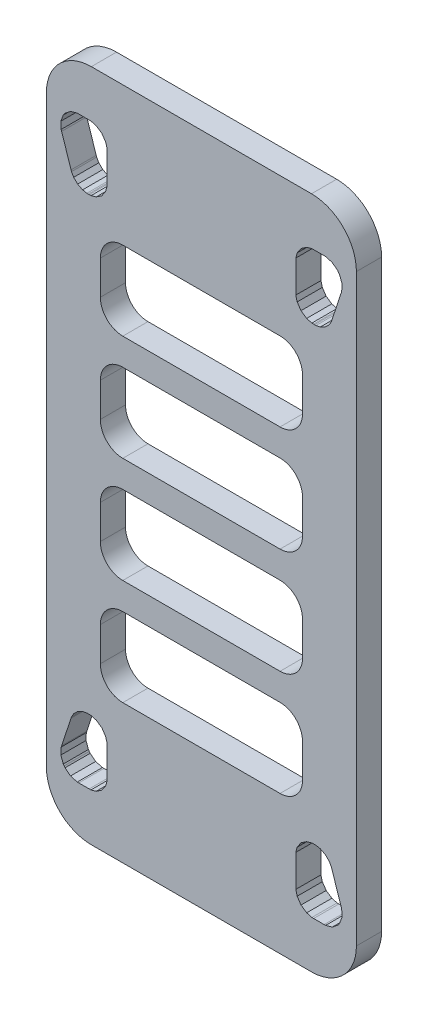
SolidWorks part; units mm, degrees
ref_plane "Front Plane" through (0, 0, 0) normal (0, 0, 1) x (1, 0, 0)
ref_plane "Top Plane" through (0, 0, 0) normal (0, 1, 0) x (1, 0, 0)
ref_plane "Right Plane" through (0, 0, 0) normal (1, 0, 0) x (0, 0, -1)
sketch "Model" plane through (0, 0, 0) normal (0, 0, 1) x (1, 0, 0)
  line L0 (59.6534, 200.5663) -> (102.2769, 95.4571) construction
  line L1 (59.6534, 95.4571) -> (102.2769, 200.5663) construction
  line L2 (58.4652, 168.561) -> (103.4652, 168.561)
  line L3 (46.4652, 73.0117) -> (115.4652, 73.0117)
  line L4 (46.4652, 73.0117) -> (46.4652, 223.0117)
  line L5 (46.4652, 223.0117) -> (115.4652, 223.0117)
  line L6 (115.4652, 73.0117) -> (115.4652, 223.0117)
  line L7 (46.4652, 73.0117) -> (115.4652, 223.0117) construction
  line L8 (46.4652, 223.0117) -> (115.4652, 73.0117) construction
  line L9 (58.4652, 192.1103) -> (103.4652, 192.1103)
  line L10 (58.4652, 192.1103) -> (58.4652, 174.561)
  line L11 (58.4652, 174.561) -> (103.4652, 174.561)
  line L12 (103.4652, 192.1103) -> (103.4652, 174.561)
  line L13 (58.4652, 168.561) -> (58.4652, 151.0117)
  line L14 (58.4652, 151.0117) -> (103.4652, 151.0117)
  line L15 (103.4652, 168.561) -> (103.4652, 151.0117)
  line L16 (46.4652, 148.0117) -> (115.4652, 148.0117) construction
  line L17 (103.4652, 127.4624) -> (103.4652, 145.0117)
  line L18 (58.4652, 145.0117) -> (103.4652, 145.0117)
  line L19 (58.4652, 127.4624) -> (58.4652, 145.0117)
  line L20 (103.4652, 103.9131) -> (103.4652, 121.4624)
  line L21 (58.4652, 121.4624) -> (103.4652, 121.4624)
  line L22 (58.4652, 103.9131) -> (58.4652, 121.4624)
  line L23 (58.4652, 103.9131) -> (103.4652, 103.9131)
  line L24 (58.4652, 127.4624) -> (103.4652, 127.4624)
  line L750 (105.9261, 198.1103) -> (106.1466, 198.1083)
  line L751 (106.1466, 198.1083) -> (106.4629, 198.1063)
  line L752 (106.4629, 198.1063) -> (107.4142, 198.2935)
  line L753 (107.4142, 198.2935) -> (108.5206, 198.8449)
  line L754 (108.5206, 198.8449) -> (109.3988, 199.7143)
  line L755 (109.3988, 199.7143) -> (109.8858, 200.5555)
  line L756 (109.8858, 200.5555) -> (109.985, 200.8552)
  line L757 (109.985, 200.8552) -> (112.0871, 207.2269)
  line L758 (112.0871, 207.2269) -> (112.1901, 207.5429)
  line L759 (112.1901, 207.5429) -> (112.252, 209.1014)
  line L760 (112.252, 209.1014) -> (111.7087, 210.5477)
  line L761 (111.7087, 210.5477) -> (111.5152, 210.8165)
  line L762 (111.5152, 210.8165) -> (111.32, 211.086)
  line L763 (111.32, 211.086) -> (110.0985, 212.0528)
  line L764 (110.0985, 212.0528) -> (108.5995, 212.4804)
  line L765 (108.5995, 212.4804) -> (108.269, 212.4799)
  line L766 (108.269, 212.4799) -> (105.9481, 212.4799)
  line L767 (105.9481, 212.4799) -> (105.5607, 212.4691)
  line L768 (105.5607, 212.4691) -> (104.3973, 212.1494)
  line L769 (104.3973, 212.1494) -> (103.1334, 211.2912)
  line L770 (103.1334, 211.2912) -> (102.2786, 210.0219)
  line L771 (102.2786, 210.0219) -> (101.9664, 208.8586)
  line L772 (101.9664, 208.8586) -> (101.9664, 208.4691)
  line L773 (101.9664, 208.4691) -> (101.9664, 202.1103)
  line L774 (101.9664, 202.1103) -> (101.9664, 201.7239)
  line L775 (101.9664, 201.7239) -> (102.2769, 200.5663)
  line L776 (102.2769, 200.5663) -> (103.124, 199.2987)
  line L777 (103.124, 199.2987) -> (104.3828, 198.4371)
  line L778 (104.3828, 198.4371) -> (105.5383, 198.1134)
  line L779 (105.5383, 198.1134) -> (105.9261, 198.1103)
  line L780 (56.0063, 198.1103) -> (55.7862, 198.1083)
  line L781 (55.7862, 198.1083) -> (55.4681, 198.1063)
  line L782 (55.4681, 198.1063) -> (54.5158, 198.2935)
  line L783 (54.5158, 198.2935) -> (53.4101, 198.8449)
  line L784 (53.4101, 198.8449) -> (52.5319, 199.7143)
  line L785 (52.5319, 199.7143) -> (52.0466, 200.5555)
  line L786 (52.0466, 200.5555) -> (51.9474, 200.8552)
  line L787 (51.9474, 200.8552) -> (49.8456, 207.2269)
  line L788 (49.8456, 207.2269) -> (49.741, 207.5429)
  line L789 (49.741, 207.5429) -> (49.6783, 209.1014)
  line L790 (49.6783, 209.1014) -> (50.2131, 210.5638)
  line L791 (50.2131, 210.5638) -> (50.4095, 210.8317)
  line L792 (50.4095, 210.8317) -> (50.6042, 211.1002)
  line L793 (50.6042, 211.1002) -> (51.8299, 212.0614)
  line L794 (51.8299, 212.0614) -> (53.3312, 212.482)
  line L795 (53.3312, 212.482) -> (53.6637, 212.4799)
  line L796 (53.6637, 212.4799) -> (55.984, 212.4799)
  line L797 (55.984, 212.4799) -> (56.37, 212.4818)
  line L798 (56.37, 212.4818) -> (57.5345, 212.1675)
  line L799 (57.5345, 212.1675) -> (58.8048, 211.3152)
  line L800 (58.8048, 211.3152) -> (59.6628, 210.0499)
  line L801 (59.6628, 210.0499) -> (59.9825, 208.8881)
  line L802 (59.9825, 208.8881) -> (59.9656, 208.4691)
  line L803 (59.9656, 208.4691) -> (59.9656, 202.1103)
  line L804 (59.9656, 202.1103) -> (59.9656, 201.7239)
  line L805 (59.9656, 201.7239) -> (59.6534, 200.5663)
  line L806 (59.6534, 200.5663) -> (58.8064, 199.2987)
  line L807 (58.8064, 199.2987) -> (57.5479, 198.4371)
  line L808 (57.5479, 198.4371) -> (56.3924, 198.1134)
  line L809 (56.3924, 198.1134) -> (56.0063, 198.1103)
  line L810 (105.9261, 97.9101) -> (106.1466, 97.9118)
  line L811 (106.1466, 97.9118) -> (106.4629, 97.9155)
  line L812 (106.4629, 97.9155) -> (107.4142, 97.7279)
  line L813 (107.4142, 97.7279) -> (108.5206, 97.1772)
  line L814 (108.5206, 97.1772) -> (109.3988, 96.3078)
  line L815 (109.3988, 96.3078) -> (109.8858, 95.4666)
  line L816 (109.8858, 95.4666) -> (109.985, 95.1648)
  line L817 (109.985, 95.1648) -> (112.0871, 88.7928)
  line L818 (112.0871, 88.7928) -> (112.1901, 88.4785)
  line L819 (112.1901, 88.4785) -> (112.252, 86.9227)
  line L820 (112.252, 86.9227) -> (111.7098, 85.4737)
  line L821 (111.7098, 85.4737) -> (111.5161, 85.203)
  line L822 (111.5161, 85.203) -> (111.3208, 84.934)
  line L823 (111.3208, 84.934) -> (110.0988, 83.9682)
  line L824 (110.0988, 83.9682) -> (108.5995, 83.5411)
  line L825 (108.5995, 83.5411) -> (108.269, 83.5415)
  line L826 (108.269, 83.5415) -> (105.9481, 83.5415)
  line L827 (105.9481, 83.5415) -> (105.5607, 83.553)
  line L828 (105.5607, 83.553) -> (104.3973, 83.8723)
  line L829 (104.3973, 83.8723) -> (103.1334, 84.7325)
  line L830 (103.1334, 84.7325) -> (102.2786, 86.0022)
  line L831 (102.2786, 86.0022) -> (101.9664, 87.1648)
  line L832 (101.9664, 87.1648) -> (101.9664, 87.5509)
  line L833 (101.9664, 87.5509) -> (101.9664, 93.9101)
  line L834 (101.9664, 93.9101) -> (101.9664, 94.2975)
  line L835 (101.9664, 94.2975) -> (102.2769, 95.4571)
  line L836 (102.2769, 95.4571) -> (103.124, 96.7234)
  line L837 (103.124, 96.7234) -> (104.3828, 97.5849)
  line L838 (104.3828, 97.5849) -> (105.5383, 97.9063)
  line L839 (105.5383, 97.9063) -> (105.9261, 97.9101)
  line L840 (56.0063, 97.9101) -> (55.7862, 97.9118)
  line L841 (55.7862, 97.9118) -> (55.4681, 97.9155)
  line L842 (55.4681, 97.9155) -> (54.5158, 97.7279)
  line L843 (54.5158, 97.7279) -> (53.4101, 97.1772)
  line L844 (53.4101, 97.1772) -> (52.5319, 96.3078)
  line L845 (52.5319, 96.3078) -> (52.0466, 95.4666)
  line L846 (52.0466, 95.4666) -> (51.9474, 95.1648)
  line L847 (51.9474, 95.1648) -> (49.8456, 88.7928)
  line L848 (49.8456, 88.7928) -> (49.741, 88.4785)
  line L849 (49.741, 88.4785) -> (49.6783, 86.9227)
  line L850 (49.6783, 86.9227) -> (50.2131, 85.4597)
  line L851 (50.2131, 85.4597) -> (50.4095, 85.1897)
  line L852 (50.4095, 85.1897) -> (50.6042, 84.9215)
  line L853 (50.6042, 84.9215) -> (51.8299, 83.9607)
  line L854 (51.8299, 83.9607) -> (53.3312, 83.5398)
  line L855 (53.3312, 83.5398) -> (53.6637, 83.5415)
  line L856 (53.6637, 83.5415) -> (55.984, 83.5415)
  line L857 (55.984, 83.5415) -> (56.37, 83.5419)
  line L858 (56.37, 83.5419) -> (57.5343, 83.8565)
  line L859 (57.5343, 83.8565) -> (58.8041, 84.7115)
  line L860 (58.8041, 84.7115) -> (59.6614, 85.9777)
  line L861 (59.6614, 85.9777) -> (59.9804, 87.1391)
  line L862 (59.9804, 87.1391) -> (59.982, 87.5251)
  line L863 (59.982, 87.5251) -> (59.982, 93.8843)
  line L864 (59.982, 93.8843) -> (59.982, 94.2717)
  line L865 (59.982, 94.2717) -> (59.6534, 95.4571)
  line L866 (59.6534, 95.4571) -> (58.8064, 96.7234)
  line L867 (58.8064, 96.7234) -> (57.5479, 97.5849)
  line L868 (57.5479, 97.5849) -> (56.3924, 97.9063)
  line L869 (56.3924, 97.9063) -> (56.0063, 97.9101)
  point P0 (80.9652, 148.0117)
  dimension "D5" = 6
  dimension "D6" = 6
  dimension "D7" = 3
  dimension "D1" = 69
  dimension "D2" = 12
  dimension "D3" = 150
  dimension "D4" = 12
extrude "Boss-Extrude1" add sketch "Model" along normal blind 5.6
fillet "Fillet1" radius 10 4 edges at (115.4652, 73.0117, 2.8) (46.4652, 73.0117, 2.8) (46.4652, 223.0117, 2.8) (115.4652, 223.0117, 2.8)
fillet "Fillet2" radius 5 16 edges at (103.4652, 192.1103, 2.8) (103.4652, 168.561, 2.8) (103.4652, 145.0117, 2.8) (103.4652, 121.4624, 2.8) (103.4652, 103.9131, 2.8) (103.4652, 127.4624, 2.8) (103.4652, 151.0117, 2.8) (103.4652, 174.561, 2.8) (58.4652, 103.9131, 2.8) (58.4652, 127.4624, 2.8) (58.4652, 151.0117, 2.8) (58.4652, 121.4624, 2.8) (58.4652, 145.0117, 2.8) (58.4652, 168.561, 2.8) (58.4652, 192.1103, 2.8) (58.4652, 174.561, 2.8)
